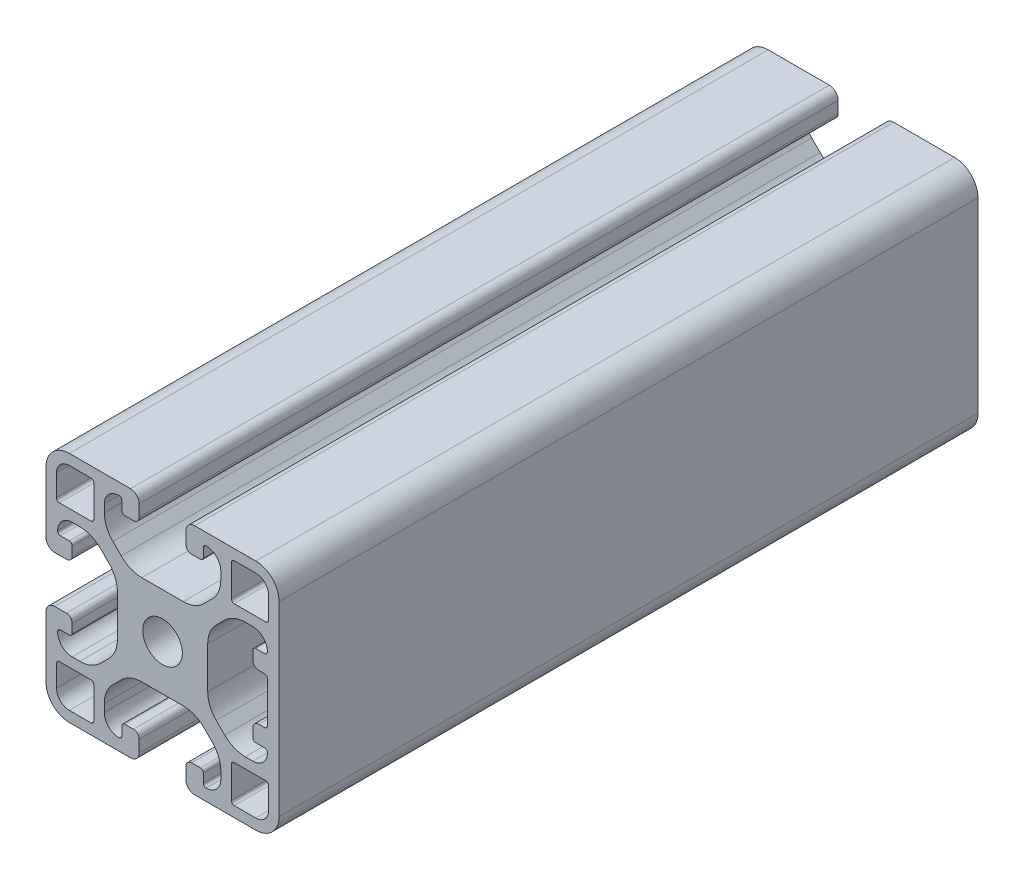
SolidWorks part; units mm, degrees
ref_plane "Piano frontale" through (0, 0, 0) normal (0, 0, 1) x (1, 0, 0)
ref_plane "Piano superiore" through (0, 0, 0) normal (0, 1, 0) x (1, 0, 0)
ref_plane "Piano destro" through (0, 0, 0) normal (1, 0, 0) x (0, 0, -1)
ref_plane "Piano1" through (0, 0, -340) normal (0, 0, -1) x (-1, 0, 0)
sketch "Schizzo1" plane through (0, 0, -340) normal (0, 0, -1) x (-1, 0, 0)
  line L0 (-12.3, -18.2) -> (-16, -18.2)
  line L1 (-18.2, -16) -> (-18.2, -12.3)
  line L2 (-17.7, -11.8) -> (-12.3, -11.8)
  line L3 (-11.8, -12.3) -> (-11.8, -17.7)
  line L4 (-11.8, 17.7) -> (-11.8, 12.3)
  line L5 (-12.3, 11.8) -> (-17.7, 11.8)
  line L6 (-18.2, 12.3) -> (-18.2, 16)
  line L7 (-16, 18.2) -> (-12.3, 18.2)
  line L8 (18.2, 16) -> (18.2, 12.3)
  line L9 (17.7, 11.8) -> (12.3, 11.8)
  line L10 (11.8, 12.3) -> (11.8, 17.7)
  line L11 (12.3, 18.2) -> (16, 18.2)
  line L12 (6.5, -15.5) -> (5, -15.5)
  line L13 (4, -16.5) -> (4, -18.5)
  line L14 (5.5, -20) -> (16, -20)
  line L15 (20, -16) -> (20, -5.5)
  line L16 (18.5, -4) -> (16.5, -4)
  line L17 (15.5, -5) -> (15.5, -6.5)
  line L18 (16, -7) -> (17.55, -7)
  line L19 (18, -7.45) -> (18, -7.5)
  line L20 (15.5, -10) -> (14.1924, -10)
  line L21 (10.6569, -8.5355) -> (9.2145, -7.0931)
  line L22 (7.75, -3.5576) -> (7.75, 3.5576)
  line L23 (9.2145, 7.0931) -> (10.6569, 8.5355)
  line L24 (14.1924, 10) -> (15.5, 10)
  line L25 (18, 7.5) -> (18, 7.45)
  line L26 (17.55, 7) -> (16, 7)
  line L27 (15.5, 6.5) -> (15.5, 5)
  line L28 (16.5, 4) -> (18.5, 4)
  line L29 (20, 5.5) -> (20, 16)
  line L30 (16, 20) -> (5.5, 20)
  line L31 (4, 18.5) -> (4, 16.5)
  line L32 (5, 15.5) -> (6.5, 15.5)
  line L33 (7, 16) -> (7, 17.55)
  line L34 (7.45, 18) -> (7.5, 18)
  line L35 (10, 15.5) -> (10, 14.1924)
  line L36 (8.5355, 10.6569) -> (7.0931, 9.2145)
  line L37 (3.5576, 7.75) -> (-3.5576, 7.75)
  line L38 (-7.0931, 9.2145) -> (-8.5355, 10.6569)
  line L39 (-10, 14.1924) -> (-10, 15.5)
  line L40 (-7.5, 18) -> (-7.45, 18)
  line L41 (-7, 17.55) -> (-7, 16)
  line L42 (-6.5, 15.5) -> (-5, 15.5)
  line L43 (-4, 16.5) -> (-4, 18.5)
  line L44 (-5.5, 20) -> (-16, 20)
  line L45 (-20, 16) -> (-20, -16)
  line L46 (-16, -20) -> (-5.5, -20)
  line L47 (-4, -18.5) -> (-4, -16.5)
  line L48 (-5, -15.5) -> (-6.5, -15.5)
  line L49 (-7, -16) -> (-7, -17.55)
  line L50 (-7.45, -18) -> (-7.5, -18)
  line L51 (-10, -15.5) -> (-10, -14.1924)
  line L52 (-8.5355, -10.6569) -> (-7.0931, -9.2145)
  line L53 (-3.5576, -7.75) -> (3.5576, -7.75)
  line L54 (7.0931, -9.2145) -> (8.5355, -10.6569)
  line L55 (10, -14.1924) -> (10, -15.5)
  line L56 (7.5, -18) -> (7.45, -18)
  line L57 (7, -17.55) -> (7, -16)
  line L58 (18.2, -12.3) -> (18.2, -16)
  line L59 (16, -18.2) -> (12.3, -18.2)
  line L60 (11.8, -17.7) -> (11.8, -12.3)
  line L61 (12.3, -11.8) -> (17.7, -11.8)
  line L62 (-16, 7) -> (-17.5, 7)
  line L63 (-15.5, 10) -> (-14.1924, 10)
  line L64 (-10.6569, 8.5355) -> (-9.2145, 7.0931)
  line L65 (-7.75, 3.5576) -> (-7.75, -3.5576)
  line L66 (-9.2145, -7.0931) -> (-10.6569, -8.5355)
  line L67 (-14.1924, -10) -> (-15.5, -10)
  line L68 (-17.5, -7) -> (-16, -7)
  line L69 (-15.5, -6.5) -> (-15.5, -5)
  line L70 (-16.5, -4) -> (-17.5, -4)
  line L71 (-18, -3.5) -> (-18, 3.5)
  line L72 (-17.5, 4) -> (-16.5, 4)
  line L73 (-15.5, 5) -> (-15.5, 6.5)
  arc A0 (-16, -18.2) -> (-18.2, -16) centre (-16, -16) cw
  arc A1 (-18.2, -12.3) -> (-17.7, -11.8) centre (-17.7, -12.3) cw
  arc A2 (-12.3, -11.8) -> (-11.8, -12.3) centre (-12.3, -12.3) cw
  arc A3 (-11.8, -17.7) -> (-12.3, -18.2) centre (-12.3, -17.7) cw
  arc A4 (-12.3, 18.2) -> (-11.8, 17.7) centre (-12.3, 17.7) cw
  arc A5 (-11.8, 12.3) -> (-12.3, 11.8) centre (-12.3, 12.3) cw
  arc A6 (-17.7, 11.8) -> (-18.2, 12.3) centre (-17.7, 12.3) cw
  arc A7 (-18.2, 16) -> (-16, 18.2) centre (-16, 16) cw
  arc A8 (16, 18.2) -> (18.2, 16) centre (16, 16) cw
  arc A9 (18.2, 12.3) -> (17.7, 11.8) centre (17.7, 12.3) cw
  arc A10 (12.3, 11.8) -> (11.8, 12.3) centre (12.3, 12.3) cw
  arc A11 (11.8, 17.7) -> (12.3, 18.2) centre (12.3, 17.7) cw
  arc A12 (5, -15.5) -> (4, -16.5) centre (5, -16.5) ccw
  arc A13 (4, -18.5) -> (5.5, -20) centre (5.5, -18.5) ccw
  arc A14 (16, -20) -> (20, -16) centre (16, -16) ccw
  arc A15 (20, -5.5) -> (18.5, -4) centre (18.5, -5.5) ccw
  arc A16 (16.5, -4) -> (15.5, -5) centre (16.5, -5) ccw
  arc A17 (15.5, -6.5) -> (16, -7) centre (16, -6.5) ccw
  arc A18 (17.55, -7) -> (18, -7.45) centre (17.55, -7.45) cw
  arc A19 (18, -7.5) -> (15.5, -10) centre (15.5, -7.5) cw
  arc A20 (14.1924, -10) -> (10.6569, -8.5355) centre (14.1924, -5) cw
  arc A21 (9.2145, -7.0931) -> (7.75, -3.5576) centre (12.75, -3.5576) cw
  arc A22 (7.75, 3.5576) -> (9.2145, 7.0931) centre (12.75, 3.5576) cw
  arc A23 (10.6569, 8.5355) -> (14.1924, 10) centre (14.1924, 5) cw
  arc A24 (15.5, 10) -> (18, 7.5) centre (15.5, 7.5) cw
  arc A25 (18, 7.45) -> (17.55, 7) centre (17.55, 7.45) cw
  arc A26 (16, 7) -> (15.5, 6.5) centre (16, 6.5) ccw
  arc A27 (15.5, 5) -> (16.5, 4) centre (16.5, 5) ccw
  arc A28 (18.5, 4) -> (20, 5.5) centre (18.5, 5.5) ccw
  arc A29 (20, 16) -> (16, 20) centre (16, 16) ccw
  arc A30 (5.5, 20) -> (4, 18.5) centre (5.5, 18.5) ccw
  arc A31 (4, 16.5) -> (5, 15.5) centre (5, 16.5) ccw
  arc A32 (6.5, 15.5) -> (7, 16) centre (6.5, 16) ccw
  arc A33 (7, 17.55) -> (7.45, 18) centre (7.45, 17.55) cw
  arc A34 (7.5, 18) -> (10, 15.5) centre (7.5, 15.5) cw
  arc A35 (10, 14.1924) -> (8.5355, 10.6569) centre (5, 14.1924) cw
  arc A36 (7.0931, 9.2145) -> (3.5576, 7.75) centre (3.5576, 12.75) cw
  arc A37 (-3.5576, 7.75) -> (-7.0931, 9.2145) centre (-3.5576, 12.75) cw
  arc A38 (-8.5355, 10.6569) -> (-10, 14.1924) centre (-5, 14.1924) cw
  arc A39 (-10, 15.5) -> (-7.5, 18) centre (-7.5, 15.5) cw
  arc A40 (-7.45, 18) -> (-7, 17.55) centre (-7.45, 17.55) cw
  arc A41 (-7, 16) -> (-6.5, 15.5) centre (-6.5, 16) ccw
  arc A42 (-5, 15.5) -> (-4, 16.5) centre (-5, 16.5) ccw
  arc A43 (-4, 18.5) -> (-5.5, 20) centre (-5.5, 18.5) ccw
  arc A44 (-16, 20) -> (-20, 16) centre (-16, 16) ccw
  arc A45 (-20, -16) -> (-16, -20) centre (-16, -16) ccw
  arc A46 (-5.5, -20) -> (-4, -18.5) centre (-5.5, -18.5) ccw
  arc A47 (-4, -16.5) -> (-5, -15.5) centre (-5, -16.5) ccw
  arc A48 (-6.5, -15.5) -> (-7, -16) centre (-6.5, -16) ccw
  arc A49 (-7, -17.55) -> (-7.45, -18) centre (-7.45, -17.55) cw
  arc A50 (-7.5, -18) -> (-10, -15.5) centre (-7.5, -15.5) cw
  arc A51 (-10, -14.1924) -> (-8.5355, -10.6569) centre (-5, -14.1924) cw
  arc A52 (-7.0931, -9.2145) -> (-3.5576, -7.75) centre (-3.5576, -12.75) cw
  arc A53 (3.5576, -7.75) -> (7.0931, -9.2145) centre (3.5576, -12.75) cw
  arc A54 (8.5355, -10.6569) -> (10, -14.1924) centre (5, -14.1924) cw
  arc A55 (10, -15.5) -> (7.5, -18) centre (7.5, -15.5) cw
  arc A56 (7.45, -18) -> (7, -17.55) centre (7.45, -17.55) cw
  arc A57 (7, -16) -> (6.5, -15.5) centre (6.5, -16) ccw
  arc A58 (17.7, -11.8) -> (18.2, -12.3) centre (17.7, -12.3) cw
  arc A59 (18.2, -16) -> (16, -18.2) centre (16, -16) cw
  arc A60 (12.3, -18.2) -> (11.8, -17.7) centre (12.3, -17.7) cw
  arc A61 (11.8, -12.3) -> (12.3, -11.8) centre (12.3, -12.3) cw
  circle A62 centre (0, 0) radius 3.4
  arc A63 (-15.5, 6.5) -> (-16, 7) centre (-16, 6.5) ccw
  arc A64 (-17.5, 7) -> (-18, 7.5) centre (-17.5, 7.5) cw
  arc A65 (-18, 7.5) -> (-15.5, 10) centre (-15.5, 7.5) cw
  arc A66 (-14.1924, 10) -> (-10.6569, 8.5355) centre (-14.1924, 5) cw
  arc A67 (-9.2145, 7.0931) -> (-7.75, 3.5576) centre (-12.75, 3.5576) cw
  arc A68 (-7.75, -3.5576) -> (-9.2145, -7.0931) centre (-12.75, -3.5576) cw
  arc A69 (-10.6569, -8.5355) -> (-14.1924, -10) centre (-14.1924, -5) cw
  arc A70 (-15.5, -10) -> (-18, -7.5) centre (-15.5, -7.5) cw
  arc A71 (-18, -7.5) -> (-17.5, -7) centre (-17.5, -7.5) cw
  arc A72 (-16, -7) -> (-15.5, -6.5) centre (-16, -6.5) ccw
  arc A73 (-15.5, -5) -> (-16.5, -4) centre (-16.5, -5) ccw
  arc A74 (-17.5, -4) -> (-18, -3.5) centre (-17.5, -3.5) cw
  arc A75 (-18, 3.5) -> (-17.5, 4) centre (-17.5, 3.5) cw
  arc A76 (-16.5, 4) -> (-15.5, 5) centre (-16.5, 5) ccw
extrude "Estrusione-Estrusione1" add sketch "Schizzo1" against normal blind 119.94
